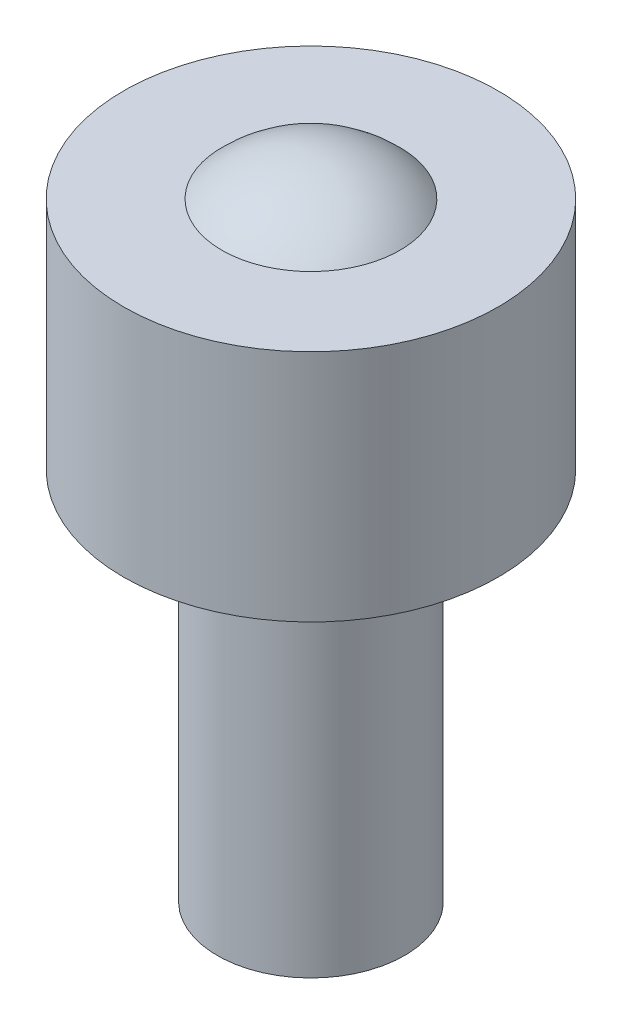
SolidWorks part; units mm, degrees
ref_plane "Plan de face" through (0, 0, 0) normal (0, 0, 1) x (1, 0, 0)
ref_plane "Plan de dessus" through (0, 0, 0) normal (0, 1, 0) x (1, 0, 0)
ref_plane "Plan de droite" through (0, 0, 0) normal (1, 0, 0) x (0, 0, -1)
sketch "Esquisse1" plane through (0, 0, 0) normal (0, 1, 0) x (1, 0, 0)
  circle A0 centre (0, 0) radius 6
  dimension "D1" = 12
extrude "Boss.-Extru.1" add sketch "Esquisse1" along normal blind 7.5
sketch "Esquisse2" plane through (0, 0, 0) normal (1, 0, 0) x (0, 0, -1)
  line L0 (0, 0) -> (0, 8.7) construction
  line L1 (6, 7.5) -> (-6, 7.5) construction
  line L2 (0, 0.7) -> (0, 8.7)
  arc A1 (0, 8.7) -> (0, 0.7) centre (0, 4.7) ccw
  dimension "D1" = 4
  dimension "D2" = 1.2
revolve "Révolution6" add sketch "Esquisse2" angle 360 about L0
sketch "Esquisse3" plane through (0, 0, 0) normal (0, -1, 0) x (1, 0, 0)
  circle A0 centre (0, 0) radius 3
  dimension "D1" = 6
extrude "Boss.-Extru.2" add sketch "Esquisse3" along normal blind 12
ref_plane "Plan1" through (0, 8.7, 0) normal (0, 1, 0) x (1, 0, 0)
